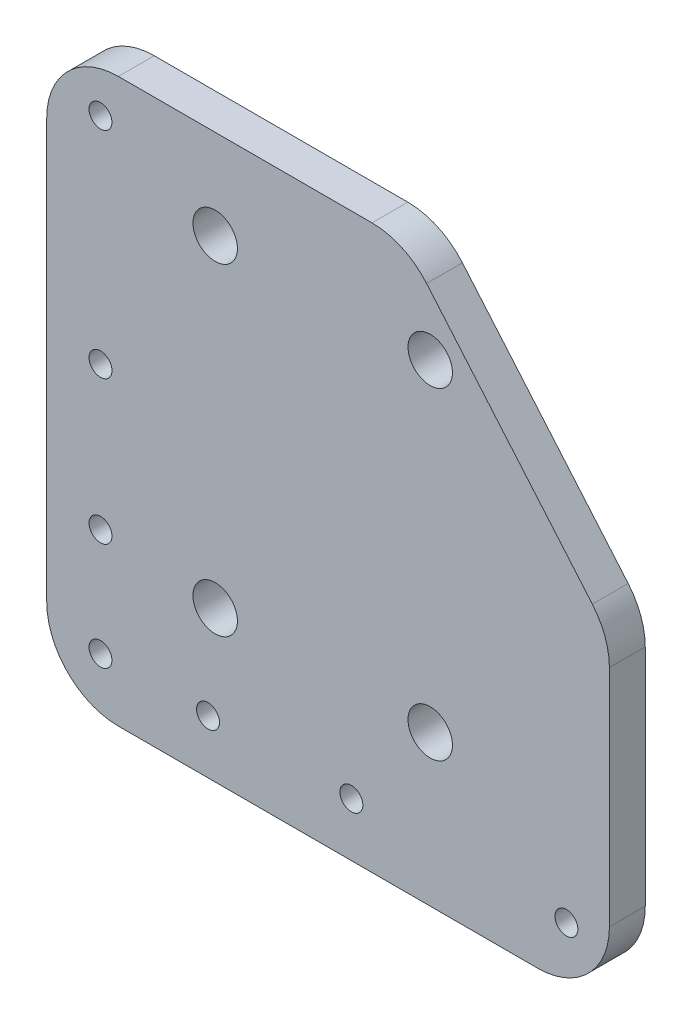
SolidWorks part; units mm, degrees
ref_plane "前视基准面" through (0, 0, 0) normal (0, 0, 1) x (1, 0, 0)
ref_plane "上视基准面" through (0, 0, 0) normal (0, 1, 0) x (1, 0, 0)
ref_plane "右视基准面" through (0, 0, 0) normal (1, 0, 0) x (0, 0, -1)
sketch "草图1" plane through (0, 0, 0) normal (0, 0, 1) x (1, 0, 0)
  line L0 (0, 65) -> (0, 0) construction
  line L1 (0, 0) -> (65, 0) construction
  line L2 (-7.5, 71) -> (-7.5, -7.5)
  line L3 (-7.5, -7.5) -> (71, -7.5)
  line L4 (71, -7.5) -> (71, 37.5)
  line L5 (71, 37.5) -> (42.5, 71)
  line L6 (42.5, 71) -> (-7.5, 71)
  line L8 (16, 13.5) -> (46, 13.5) construction
  line L9 (16, 13.5) -> (16, 58.5) construction
  line L10 (16, 58.5) -> (46, 58.5) construction
  line L11 (46, 13.5) -> (46, 58.5) construction
  line L12 (16, 13.5) -> (46, 58.5) construction
  line L13 (16, 58.5) -> (46, 13.5) construction
  circle A0 centre (0, 0) radius 1.6
  circle A1 centre (0, 15) radius 1.6
  circle A2 centre (0, 35) radius 1.6
  circle A3 centre (0, 65) radius 1.6
  circle A4 centre (15, 0) radius 1.6
  circle A5 centre (35, 0) radius 1.6
  circle A6 centre (65, 0) radius 1.6
  circle A7 centre (16, 58.5) radius 3.1
  circle A8 centre (16, 13.5) radius 3.1
  circle A9 centre (46, 13.5) radius 3.1
  circle A10 centre (46, 58.5) radius 3.1
  point P20 (31, 36)
  dimension "D1" = 3.2
  dimension "D3" = 20
  dimension "D4" = 30
  dimension "D5" = 30
  dimension "D6" = 20
  dimension "D7" = 15
  dimension "D8" = 6.2
  dimension "D13" = 6
  dimension "D2" = 15
  dimension "D9" = 30
  dimension "D10" = 45
  dimension "D11" = 36
  dimension "D12" = 31
  dimension "D14" = 7.5
  dimension "D15" = 7.5
  dimension "D16" = 6
  dimension "D17" = 50
  dimension "D18" = 45
extrude "凸台-拉伸1" add sketch "草图1" along normal blind 5
fillet "圆角1" radius 10 5 edges at (71, 37.5, 2.5) (71, -7.5, 2.5) (-7.5, -7.5, 2.5) (-7.5, 71, 2.5) (42.5, 71, 2.5)
